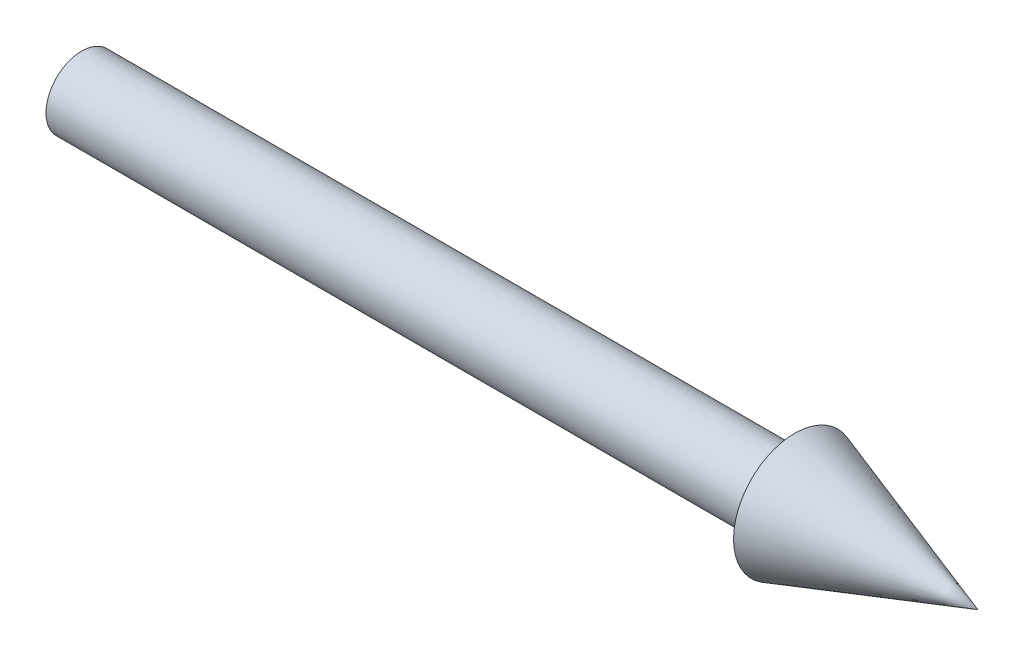
SolidWorks part; units mm, degrees
ref_plane "前视基准面" through (0, 0, 0) normal (0, 0, 1) x (1, 0, 0)
ref_plane "上视基准面" through (0, 0, 0) normal (0, 1, 0) x (1, 0, 0)
ref_plane "右视基准面" through (0, 0, 0) normal (1, 0, 0) x (0, 0, -1)
sketch "草图1" plane through (0, 0, 0) normal (0, 1, 0) x (1, 0, 0)
  line L0 (70, -6) -> (88, 0)
  line L1 (0, 0) -> (50, 0)
  line L2 (0, 0) -> (0, -3.5)
  line L3 (0, -3.5) -> (70, -3.5)
  line L5 (50, 0) -> (88, 0)
  line L6 (70, -3.5) -> (70, -6)
  dimension "D1" = 70
  dimension "D2" = 3.5
  dimension "D3" = 2.5
  dimension "D4" = 18
revolve "旋转2" add sketch "草图1" angle 360 about L1
